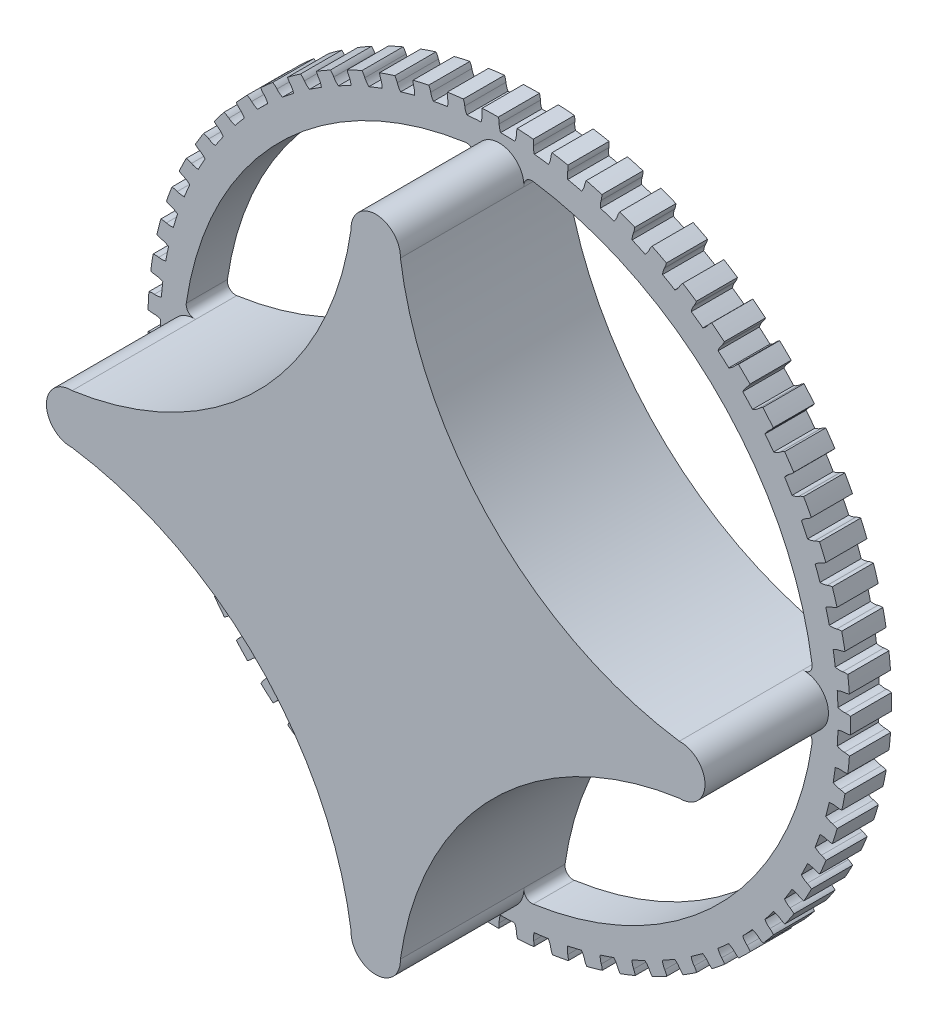
SolidWorks part; units mm, degrees
ref_plane "Alzado" through (0, 0, 0) normal (0, 0, 1) x (1, 0, 0)
ref_plane "Planta" through (0, 0, 0) normal (0, 1, 0) x (1, 0, 0)
ref_plane "Vista lateral" through (0, 0, 0) normal (1, 0, 0) x (0, 0, -1)
sketch "Croquis1" plane through (0, 0, 0) normal (0, 0, 1) x (1, 0, 0)
  circle A0 centre (0, 0) radius 40
  dimension "D1" = 80
extrude "Saliente-Extruir1" add sketch "Croquis1" along normal blind 5
sketch "Croquis2" plane through (0, 0, 5) normal (0, 0, 1) x (1, 0, 0)
  line L0 (0, 35.355) -> (35.355, -0.0007) construction
  line L1 (35.355, -0.0007) -> (0, -35.355) construction
  line L2 (0, -35.355) -> (-35.355, 0) construction
  line L3 (-35.355, 0) -> (0, 35.355) construction
  line L4 (0, 52.836) -> (0, -48.8534) construction
  line L5 (55.853, 0) -> (-59.1163, 0) construction
  arc A0 (36.8784, -2.9975) -> (36.8784, 2.9975) centre (37, 0) ccw
  circle A1 centre (0, 0) radius 35.355 construction
  arc A2 (-2.9975, 36.8784) -> (2.9975, 36.8784) centre (0, 37) cw
  circle A3 centre (0, 0) radius 40 construction
  arc A4 (36.8784, 2.9975) -> (2.9975, 36.8784) centre (42.5879, 42.5879) cw
  arc A5 (-36.8784, -2.9975) -> (-36.8784, 2.9975) centre (-37, 0) cw
  arc A6 (-36.8784, 2.9975) -> (-2.9975, 36.8784) centre (-42.5879, 42.5879) ccw
  arc A7 (36.8784, -2.9975) -> (2.9975, -36.8784) centre (42.5879, -42.5879) ccw
  arc A8 (-2.9975, -36.8784) -> (2.9975, -36.8784) centre (0, -37) ccw
  arc A9 (-36.8784, -2.9975) -> (-2.9975, -36.8784) centre (-42.5879, -42.5879) cw
  dimension "D2" = 70.71
  dimension "D3" = 3
  dimension "D5" = 3
  dimension "D7" = 40
  dimension "D1" = 50
  dimension "D4" = 37
  dimension "D6" = 37
extrude "Saliente-Extruir2" add sketch "Croquis2" along normal blind 15
sketch "Croquis3" plane through (0, 0, 5) normal (0, 0, 1) x (1, 0, 0)
  arc A0 (2.9975, -36.8784) -> (36.8784, -2.9975) centre (42.5879, -42.5879) cw
  arc A1 (2.9975, -36.8784) -> (4.13, -38.0109) centre (3.9873, -37.0211) ccw
  arc A2 (4.13, -38.0109) -> (38.0109, -4.13) centre (-1.5795, 1.5795) ccw
  arc A3 (36.8784, -2.9975) -> (38.0109, -4.13) centre (37.0211, -3.9873) cw
  arc A4 (36.8784, -2.9975) -> (2.9975, -36.8784) centre (42.5879, -42.5879) ccw construction
  arc A5 (-36.8784, -2.9975) -> (-2.9975, -36.8784) centre (-42.5879, -42.5879) cw
  arc A6 (-38.0109, -4.13) -> (-4.13, -38.0109) centre (1.5795, 1.5795) ccw
  arc A7 (-2.9975, -36.8784) -> (-4.13, -38.0109) centre (-3.9873, -37.0211) cw
  arc A8 (-36.8784, -2.9975) -> (-38.0109, -4.13) centre (-37.0211, -3.9873) ccw
  arc A9 (-2.9975, 36.8784) -> (-36.8784, 2.9975) centre (-42.5879, 42.5879) cw
  arc A10 (-4.13, 38.0109) -> (-38.0109, 4.13) centre (1.5795, -1.5795) ccw
  arc A11 (-36.8784, 2.9975) -> (-38.0109, 4.13) centre (-37.0211, 3.9873) cw
  arc A12 (-2.9975, 36.8784) -> (-4.13, 38.0109) centre (-3.9873, 37.0211) ccw
  arc A13 (36.8784, 2.9975) -> (2.9975, 36.8784) centre (42.5879, 42.5879) cw
  arc A14 (38.0109, 4.13) -> (4.13, 38.0109) centre (-1.5795, -1.5795) ccw
  arc A15 (2.9975, 36.8784) -> (4.13, 38.0109) centre (3.9873, 37.0211) cw
  arc A16 (36.8784, 2.9975) -> (38.0109, 4.13) centre (37.0211, 3.9873) ccw
  point P40 (0, 0)
  dimension "D1" = 40
  dimension "D2" = 1
  dimension "D3" = 4
extrude "Cortar-Extruir1" cut sketch "Croquis3" against normal blind 15
sketch "Croquis4" plane through (0, 0, 0) normal (0, 0, 1) x (1, 0, 0)
  circle A0 centre (0, 0) radius 40
  circle A1 centre (0, 0) radius 42.6665
  dimension "D1" = 85.333
  dimension "D2" = 80
extrude "Saliente-Extruir3" add sketch "Croquis4" along normal up to vertex
sketch "Croquis8" plane through (0, 0, 5) normal (0, 0, 1) x (1, 0, 0)
  arc A0 (2.1854, 42.6105) -> (-0.1088, 42.6664) centre (0, 0) ccw
  circle A3 centre (0, 0) radius 42.6665 construction
  arc A5 (0, 42) -> (-0.1088, 42.6664) centre (-2.0945, 42) ccw
  arc A6 (0, 42) -> (0.1731, 41.1661) centre (2.0945, 42) ccw
  arc A8 (6.4172, 42.1812) -> (4.1399, 42.4652) centre (0, 0) ccw
  arc A9 (1.9018, 41.1225) -> (2.0945, 42) centre (0, 42) ccw
  arc A10 (1.9018, 41.1225) -> (0.1731, 41.1661) centre (0, 0) ccw
  arc A11 (4.1818, 41.7913) -> (4.1399, 42.4652) centre (2.0978, 41.9998) ccw
  arc A12 (2.1854, 42.6105) -> (2.0945, 42) centre (4.189, 42) ccw
  arc A16 (6.4172, 42.1812) -> (6.2659, 41.5827) centre (8.35, 41.3742) ccw
  arc A17 (5.9869, 40.7288) -> (6.2659, 41.5827) centre (4.1818, 41.7913) ccw
  arc A18 (4.1818, 41.7913) -> (4.2711, 40.9443) centre (6.2659, 41.5827) ccw
  arc A19 (5.9869, 40.7288) -> (4.2711, 40.9443) centre (0, 0) ccw
  arc A20 (10.5852, 41.3326) -> (8.3475, 41.842) centre (0, 0) ccw
  arc A21 (8.3221, 41.1672) -> (8.3475, 41.842) centre (6.2692, 41.5823) ccw
  arc A22 (10.5852, 41.3326) -> (10.3751, 40.7522) centre (12.4281, 40.3372) ccw
  arc A23 (10.0124, 39.9303) -> (10.3751, 40.7522) centre (8.3221, 41.1672) ccw
  arc A24 (8.3221, 41.1672) -> (8.3266, 40.3156) centre (10.3751, 40.7522) ccw
  arc A25 (10.0124, 39.9303) -> (8.3266, 40.3156) centre (0, 0) ccw
  arc A26 (14.648, 40.0733) -> (12.4721, 40.8029) centre (0, 0) ccw
  arc A27 (12.3797, 40.1341) -> (12.4721, 40.8029) centre (10.3783, 40.7514) ccw
  arc A28 (14.648, 40.0733) -> (14.3812, 39.5167) centre (16.3826, 38.8993) ccw
  arc A29 (13.9384, 38.735) -> (14.3812, 39.5167) centre (12.3797, 40.1341) ccw
  arc A30 (12.3797, 40.1341) -> (12.2994, 39.2862) centre (14.3812, 39.5167) ccw
  arc A31 (13.9384, 38.735) -> (12.2994, 39.2862) centre (0, 0) ccw
  arc A32 (18.5652, 38.4157) -> (16.4728, 39.3583) centre (0, 0) ccw
  arc A33 (16.3143, 38.702) -> (16.4728, 39.3583) centre (14.3842, 39.5156) ccw
  arc A34 (18.5652, 38.4157) -> (18.2443, 37.8884) centre (20.1743, 37.0748) ccw
  arc A35 (17.7259, 37.1547) -> (18.2443, 37.8884) centre (16.3143, 38.702) ccw
  arc A36 (16.3143, 38.702) -> (16.1499, 37.8664) centre (18.2443, 37.8884) ccw
  arc A37 (17.7259, 37.1547) -> (16.1499, 37.8664) centre (0, 0) ccw
  arc A38 (22.2979, 36.3763) -> (20.3098, 37.5226) centre (0, 0) ccw
  arc A39 (20.0867, 36.8853) -> (20.3098, 37.5226) centre (18.2472, 37.887) ccw
  arc A40 (22.2979, 36.3763) -> (21.9261, 35.8836) centre (23.7655, 34.8819) ccw
  arc A41 (21.3373, 35.2051) -> (21.9261, 35.8836) centre (20.0867, 36.8853) ccw
  arc A42 (20.0867, 36.8853) -> (19.8399, 36.0702) centre (21.9261, 35.8836) ccw
  arc A43 (21.3373, 35.2051) -> (19.8399, 36.0702) centre (0, 0) ccw
  arc A44 (25.809, 33.9753) -> (23.9449, 35.3139) centre (0, 0) ccw
  arc A45 (23.6594, 34.702) -> (23.9449, 35.3139) centre (21.9289, 35.8819) ccw
  arc A46 (25.809, 33.9753) -> (25.39, 33.5222) centre (27.1206, 32.3423) ccw
  arc A47 (24.7365, 32.9057) -> (25.39, 33.5222) centre (23.6594, 34.702) ccw
  arc A48 (23.6594, 34.702) -> (23.3328, 33.9155) centre (25.39, 33.5222) ccw
  arc A49 (24.7365, 32.9057) -> (23.3328, 33.9155) centre (0, 0) ccw
  arc A50 (29.0636, 31.2368) -> (27.342, 32.7543) centre (0, 0) ccw
  arc A51 (26.9971, 32.1739) -> (27.342, 32.7543) centre (25.3926, 33.5202) ccw
  arc A52 (29.0636, 31.2368) -> (28.6016, 30.8275) centre (30.206, 29.4812) ccw
  arc A53 (27.89, 30.2792) -> (28.6016, 30.8275) centre (26.9971, 32.1739) ccw
  arc A54 (26.9971, 32.1739) -> (26.5937, 31.4238) centre (28.6016, 30.8275) ccw
  arc A55 (27.89, 30.2792) -> (26.5937, 31.4238) centre (0, 0) ccw
  arc A56 (32.0294, 28.1877) -> (30.4674, 29.8691) centre (0, 0) ccw
  arc A57 (30.0664, 29.3259) -> (30.4674, 29.8691) centre (28.604, 30.8253) ccw
  arc A58 (32.0294, 28.1877) -> (31.5289, 27.8266) centre (32.9913, 26.3272) ccw
  arc A59 (30.7662, 27.3518) -> (31.5289, 27.8266) centre (30.0664, 29.3259) ccw
  arc A60 (30.0664, 29.3259) -> (29.5904, 28.6198) centre (31.5289, 27.8266) ccw
  arc A61 (30.7662, 27.3518) -> (29.5904, 28.6198) centre (0, 0) ccw
  arc A62 (34.6768, 24.8586) -> (33.2901, 26.6871) centre (0, 0) ccw
  arc A63 (32.8369, 26.1866) -> (33.2901, 26.6871) centre (31.531, 27.8241) ccw
  arc A64 (34.6768, 24.8586) -> (34.1428, 24.549) centre (35.4487, 22.9115) ccw
  arc A65 (33.3367, 24.1526) -> (34.1428, 24.549) centre (32.8369, 26.1866) ccw
  arc A66 (32.8369, 26.1866) -> (32.2929, 25.5313) centre (34.1428, 24.549) ccw
  arc A67 (33.3367, 24.1526) -> (32.2929, 25.5313) centre (0, 0) ccw
  arc A68 (36.9796, 21.2823) -> (35.7818, 23.2399) centre (0, 0) ccw
  arc A69 (35.2811, 22.7869) -> (35.7818, 23.2399) centre (34.1447, 24.5464) ccw
  arc A70 (36.9796, 21.2823) -> (36.4175, 21.0275) centre (37.5538, 19.2681) ccw
  arc A71 (35.5758, 20.7133) -> (36.4175, 21.0275) centre (35.2811, 22.7869) ccw
  arc A72 (35.2811, 22.7869) -> (34.6746, 22.1891) centre (36.4175, 21.0275) ccw
  arc A73 (35.5758, 20.7133) -> (34.6746, 22.1891) centre (0, 0) ccw
  arc A74 (38.9149, 17.4946) -> (37.9179, 19.5617) centre (0, 0) ccw
  arc A75 (37.3746, 19.1608) -> (37.9179, 19.5617) centre (36.4191, 21.0247) ccw
  arc A76 (38.9149, 17.4946) -> (38.3301, 17.297) centre (39.2857, 15.4332) ccw
  arc A77 (37.4614, 17.0681) -> (38.3301, 17.297) centre (37.3746, 19.1608) ccw
  arc A78 (37.3746, 19.1608) -> (36.7116, 18.6264) centre (38.3301, 17.297) ccw
  arc A79 (37.4614, 17.0681) -> (36.7116, 18.6264) centre (0, 0) ccw
  arc A80 (40.4634, 13.533) -> (39.6772, 15.6891) centre (0, 0) ccw
  arc A81 (39.0967, 15.3443) -> (39.6772, 15.6891) centre (38.3315, 17.294) ccw
  arc A82 (40.4634, 13.533) -> (39.8619, 13.3946) centre (40.6271, 11.4449) ccw
  arc A83 (38.9747, 13.2534) -> (39.8619, 13.3946) centre (39.0967, 15.3443) ccw
  arc A84 (39.0967, 15.3443) -> (38.3837, 14.8785) centre (39.8619, 13.3946) ccw
  arc A85 (38.9747, 13.2534) -> (38.3837, 14.8785) centre (0, 0) ccw
  arc A86 (41.6098, 9.4369) -> (41.0422, 11.6605) centre (0, 0) ccw
  arc A87 (40.4302, 11.3753) -> (41.0422, 11.6605) centre (39.8629, 13.3915) ccw
  arc A88 (41.6098, 9.4369) -> (40.9975, 9.3591) centre (41.5648, 7.3429) ccw
  arc A89 (40.1007, 9.3069) -> (40.9975, 9.3591) centre (40.4302, 11.3753) ccw
  arc A90 (40.4302, 11.3753) -> (39.6744, 10.9828) centre (40.9975, 9.3591) ccw
  arc A91 (40.1007, 9.3069) -> (39.6744, 10.9828) centre (0, 0) ccw
  arc A92 (42.3426, 5.247) -> (41.9993, 7.5161) centre (0, 0) ccw
  arc A93 (41.3619, 7.2932) -> (41.9993, 7.5161) centre (40.9982, 9.3559) ccw
  arc A94 (42.3426, 5.247) -> (41.7256, 5.2305) centre (42.0893, 3.1679) ccw
  arc A95 (40.8281, 5.2679) -> (41.7256, 5.2305) centre (41.3619, 7.2932) ccw
  arc A96 (41.3619, 7.2932) -> (40.5708, 6.9779) centre (41.7256, 5.2305) ccw
  arc A97 (40.8281, 5.2679) -> (40.5708, 6.9779) centre (0, 0) ccw
  arc A98 (42.6547, 1.005) -> (42.5389, 3.297) centre (0, 0) ccw
  arc A99 (41.8826, 3.1387) -> (42.5389, 3.297) centre (41.726, 5.2273) ccw
  arc A100 (42.6547, 1.005) -> (42.0391, 1.05) centre (42.1956, -1.0386) ccw
  arc A101 (41.1497, 1.1766) -> (42.0391, 1.05) centre (41.8826, 3.1387) ccw
  arc A102 (41.8826, 3.1387) -> (41.064, 2.9037) centre (42.0391, 1.05) ccw
  arc A103 (41.1497, 1.1766) -> (41.064, 2.9037) centre (0, 0) ccw
  arc A104 (42.5428, -3.2471) -> (42.6558, -0.9549) centre (0, 0) ccw
  arc A105 (41.9869, -1.0471) -> (42.6558, -0.9549) centre (42.0392, 1.0468) ccw
  arc A106 (42.5428, -3.2471) -> (41.9347, -3.1409) centre (41.8825, -5.2348) ccw
  arc A107 (41.0623, -2.9265) -> (41.9347, -3.1409) centre (41.9869, -1.0471) ccw
  arc A108 (41.9869, -1.0471) -> (41.149, -1.1994) centre (41.9347, -3.1409) ccw
  arc A109 (41.0623, -2.9265) -> (41.149, -1.1994) centre (0, 0) ccw
  arc A110 (42.0081, -7.4668) -> (42.3488, -5.1973) centre (0, 0) ccw
  arc A111 (41.674, -5.2224) -> (42.3488, -5.1973) centre (41.9345, -3.1442) ccw
  arc A112 (42.0081, -7.4668) -> (41.4136, -7.3007) centre (41.1532, -9.3789) ccw
  arc A113 (40.5669, -7.0004) -> (41.4136, -7.3007) centre (41.674, -5.2224) ccw
  arc A114 (41.674, -5.2224) -> (40.8251, -5.2906) centre (41.4136, -7.3007) ccw
  arc A115 (40.5669, -7.0004) -> (40.8251, -5.2906) centre (0, 0) ccw
  arc A116 (41.0559, -11.6124) -> (41.6208, -9.3881) centre (0, 0) ccw
  arc A117 (40.947, -9.3459) -> (41.6208, -9.3881) centre (41.413, -7.3039) ccw
  arc A118 (41.0559, -11.6124) -> (40.4809, -11.3879) centre (40.0148, -13.4299) ccw
  arc A119 (39.6683, -11.0048) -> (40.4809, -11.3879) centre (40.947, -9.3459) ccw
  arc A120 (40.947, -9.3459) -> (40.0955, -9.3291) centre (40.4809, -11.3879) ccw
  arc A121 (39.6683, -11.0048) -> (40.0955, -9.3291) centre (0, 0) ccw
  arc A122 (39.6956, -15.6425) -> (40.4793, -13.4855) centre (0, 0) ccw
  arc A123 (39.8129, -13.3764) -> (40.4793, -13.4855) centre (40.48, -11.391) ccw
  arc A124 (39.6956, -15.6425) -> (39.1459, -15.3619) centre (38.4788, -17.3473) ccw
  arc A125 (38.3755, -14.8998) -> (39.1459, -15.3619) centre (39.8129, -13.3764) ccw
  arc A126 (39.8129, -13.3764) -> (38.9674, -13.275) centre (39.1459, -15.3619) ccw
  arc A127 (38.3755, -14.8998) -> (38.9674, -13.275) centre (0, 0) ccw
  arc A128 (37.9409, -19.5172) -> (38.9354, -17.4489) centre (0, 0) ccw
  arc A129 (38.2832, -17.2741) -> (38.9354, -17.4489) centre (39.1447, -15.3649) ccw
  arc A130 (37.9409, -19.5172) -> (37.4218, -19.1832) centre (36.5604, -21.0924) ccw
  arc A131 (36.7012, -18.6467) -> (37.4218, -19.1832) centre (38.2832, -17.2741) ccw
  arc A132 (38.2832, -17.2741) -> (37.452, -17.0889) centre (37.4218, -19.1832) ccw
  arc A133 (36.7012, -18.6467) -> (37.452, -17.0889) centre (0, 0) ccw
  arc A134 (35.809, -23.1979) -> (37.0046, -21.2389) centre (0, 0) ccw
  arc A135 (36.3731, -21) -> (37.0046, -21.2389) centre (37.4203, -19.1861) ccw
  arc A136 (35.809, -23.1979) -> (35.3258, -22.8139) centre (34.2786, -24.6278) ccw
  arc A137 (34.6622, -22.2083) -> (35.3258, -22.8139) centre (36.3731, -21) ccw
  arc A138 (36.3731, -21) -> (35.5643, -20.733) centre (35.3258, -22.8139) ccw
  arc A139 (34.6622, -22.2083) -> (35.5643, -20.733) centre (0, 0) ccw
  arc A140 (33.3213, -26.6481) -> (34.706, -24.8179) centre (0, 0) ccw
  arc A141 (34.1014, -24.5172) -> (34.706, -24.8179) centre (35.324, -22.8166) ccw
  arc A142 (33.3213, -26.6481) -> (32.8787, -26.2178) centre (31.6561, -27.9184) ccw
  arc A143 (32.2788, -25.5492) -> (32.8787, -26.2178) centre (34.1014, -24.5172) ccw
  arc A144 (34.1014, -24.5172) -> (33.3233, -24.1711) centre (32.8787, -26.2178) ccw
  arc A145 (32.2788, -25.5492) -> (33.3233, -24.1711) centre (0, 0) ccw
  arc A146 (30.5025, -29.8334) -> (32.0624, -28.1501) centre (0, 0) ccw
  arc A147 (31.4908, -27.7908) -> (32.0624, -28.1501) centre (32.8767, -26.2204) ccw
  arc A148 (30.5025, -29.8334) -> (30.1049, -29.3612) centre (28.719, -30.9316) ccw
  arc A149 (29.5745, -28.6362) -> (30.1049, -29.3612) centre (31.4908, -27.7908) ccw
  arc A150 (31.4908, -27.7908) -> (30.751, -27.3689) centre (30.1049, -29.3612) ccw
  arc A151 (29.5745, -28.6362) -> (30.751, -27.3689) centre (0, 0) ccw
  arc A152 (27.3805, -32.7222) -> (29.1003, -31.2026) centre (0, 0) ccw
  arc A153 (28.5673, -30.7882) -> (29.1003, -31.2026) centre (30.1026, -29.3636) ccw
  arc A154 (27.3805, -32.7222) -> (27.0319, -32.2128) centre (25.4965, -33.6374) ccw
  arc A155 (26.5763, -31.4385) -> (27.0319, -32.2128) centre (28.5673, -30.7882) ccw
  arc A156 (28.5673, -30.7882) -> (27.8732, -30.2947) centre (27.0319, -32.2128) ccw
  arc A157 (26.5763, -31.4385) -> (27.8732, -30.2947) centre (0, 0) ccw
  arc A158 (23.9863, -35.2858) -> (25.8489, -33.945) centre (0, 0) ccw
  arc A159 (25.3598, -33.4796) -> (25.8489, -33.945) centre (27.0294, -32.2149) ccw
  arc A160 (23.9863, -35.2858) -> (23.6902, -34.7442) centre (22.0206, -36.0089) ccw
  arc A161 (23.314, -33.9285) -> (23.6902, -34.7442) centre (25.3598, -33.4796) ccw
  arc A162 (25.3598, -33.4796) -> (24.7183, -32.9194) centre (23.6902, -34.7442) ccw
  arc A163 (23.314, -33.9285) -> (24.7183, -32.9194) centre (0, 0) ccw
  arc A164 (20.3538, -37.4987) -> (22.3406, -36.3501) centre (0, 0) ccw
  arc A165 (21.9003, -35.8382) -> (22.3406, -36.3501) centre (23.6875, -34.7461) ccw
  arc A166 (20.3538, -37.4987) -> (20.1131, -36.9304) centre (18.3258, -38.0225) ccw
  arc A167 (19.8199, -36.0812) -> (20.1131, -36.9304) centre (21.9003, -35.8382) ccw
  arc A168 (21.9003, -35.8382) -> (21.3177, -35.217) centre (20.1131, -36.9304) ccw
  arc A169 (19.8199, -36.0812) -> (21.3177, -35.217) centre (0, 0) ccw
  arc A170 (16.519, -39.339) -> (18.6103, -38.3938) centre (0, 0) ccw
  arc A171 (18.2231, -37.8407) -> (18.6103, -38.3938) centre (20.1102, -36.9319) ccw
  arc A172 (16.519, -39.339) -> (16.336, -38.7495) centre (14.449, -39.6582) ccw
  arc A173 (16.1289, -37.8753) -> (16.336, -38.7495) centre (18.2231, -37.8407) ccw
  arc A174 (18.2231, -37.8407) -> (17.7053, -37.1645) centre (16.336, -38.7495) ccw
  arc A175 (16.1289, -37.8753) -> (17.7053, -37.1645) centre (0, 0) ccw
  arc A176 (12.52, -40.7882) -> (14.695, -40.056) centre (0, 0) ccw
  arc A177 (14.3648, -39.4671) -> (14.695, -40.056) centre (16.333, -38.7507) ccw
  arc A178 (12.52, -40.7882) -> (12.3967, -40.1835) centre (10.4285, -40.8998) ccw
  arc A179 (12.2776, -39.293) -> (12.3967, -40.1835) centre (14.3648, -39.4671) ccw
  arc A180 (14.3648, -39.4671) -> (13.9169, -38.7427) centre (12.3967, -40.1835) ccw
  arc A181 (12.2776, -39.293) -> (13.9169, -38.7427) centre (0, 0) ccw
  arc A182 (8.3966, -41.8321) -> (10.6337, -41.3201) centre (0, 0) ccw
  arc A183 (10.3638, -40.7012) -> (10.6337, -41.3201) centre (12.3935, -40.1844) ccw
  arc A184 (8.3966, -41.8321) -> (8.3341, -41.2181) centre (6.3043, -41.7349) ccw
  arc A185 (8.3043, -40.3202) -> (8.3341, -41.2181) centre (10.3638, -40.7012) ccw
  arc A186 (10.3638, -40.7012) -> (9.9903, -39.9359) centre (8.3341, -41.2181) ccw
  arc A187 (8.3043, -40.3202) -> (9.9903, -39.9359) centre (0, 0) ccw
  arc A188 (4.1897, -42.4603) -> (6.4667, -42.1736) centre (0, 0) ccw
  arc A189 (6.2598, -41.5309) -> (6.4667, -42.1736) centre (8.3309, -41.2187) ccw
  arc A190 (4.1897, -42.4603) -> (4.1887, -41.8431) centre (2.1176, -42.1552) ccw
  arc A191 (4.2484, -40.9467) -> (4.1887, -41.8431) centre (6.2598, -41.5309) ccw
  arc A192 (6.2598, -41.5309) -> (5.9643, -40.7322) centre (4.1887, -41.8431) ccw
  arc A193 (4.2484, -40.9467) -> (5.9643, -40.7322) centre (0, 0) ccw
  arc A194 (-0.0588, -42.6665) -> (2.2354, -42.6079) centre (0, 0) ccw
  arc A195 (2.0935, -41.9478) -> (2.2354, -42.6079) centre (4.1854, -41.8434) ccw
  arc A196 (-0.0588, -42.6665) -> (0.0016, -42.0522) centre (-2.0903, -42.1566) ccw
  arc A197 (0.1503, -41.1662) -> (0.0016, -42.0522) centre (2.0935, -41.9478) ccw
  arc A198 (2.0935, -41.9478) -> (1.879, -41.1236) centre (0.0016, -42.0522) ccw
  arc A199 (0.1503, -41.1662) -> (1.879, -41.1236) centre (0, 0) ccw
  arc A200 (-4.3067, -42.4486) -> (-2.018, -42.6187) centre (0, 0) ccw
  arc A201 (-2.0935, -41.9478) -> (-2.018, -42.6187) centre (-0.0016, -42.0522) ccw
  arc A202 (-4.3067, -42.4486) -> (-4.1854, -41.8434) centre (-6.2773, -41.739) ccw
  arc A203 (-3.9493, -40.9766) -> (-4.1854, -41.8434) centre (-2.0935, -41.9478) ccw
  arc A204 (-2.0935, -41.9478) -> (-2.2249, -41.1063) centre (-4.1854, -41.8434) ccw
  arc A205 (-3.9493, -40.9766) -> (-2.2249, -41.1063) centre (0, 0) ccw
  arc A206 (-8.5118, -41.8088) -> (-6.2515, -42.206) centre (0, 0) ccw
  arc A207 (-6.2598, -41.5309) -> (-6.2515, -42.206) centre (-4.1887, -41.8431) ccw
  arc A208 (-8.5118, -41.8088) -> (-8.3309, -41.2187) centre (-10.402, -40.9066) ccw
  arc A209 (-8.0096, -40.3798) -> (-8.3309, -41.2187) centre (-6.2598, -41.5309) ccw
  arc A210 (-6.2598, -41.5309) -> (-6.3067, -40.6805) centre (-8.3309, -41.2187) ccw
  arc A211 (-8.0096, -40.3798) -> (-6.3067, -40.6805) centre (0, 0) ccw
  arc A212 (-12.6323, -40.7536) -> (-10.4228, -41.3739) centre (0, 0) ccw
  arc A213 (-10.3638, -40.7012) -> (-10.4228, -41.3739) centre (-8.3341, -41.2181) ccw
  arc A214 (-12.6323, -40.7536) -> (-12.3935, -40.1844) centre (-14.4233, -39.6676) ccw
  arc A215 (-11.9903, -39.3816) -> (-12.3935, -40.1844) centre (-10.3638, -40.7012) ccw
  arc A216 (-10.3638, -40.7012) -> (-10.3258, -39.8504) centre (-12.3935, -40.1844) ccw
  arc A217 (-11.9903, -39.3816) -> (-10.3258, -39.8504) centre (0, 0) ccw
  arc A218 (-16.6273, -39.2933) -> (-14.4905, -40.1305) centre (0, 0) ccw
  arc A219 (-14.3648, -39.4671) -> (-14.4905, -40.1305) centre (-12.3967, -40.1835) ccw
  arc A220 (-16.6273, -39.2933) -> (-16.333, -38.7507) centre (-18.3012, -38.0344) ccw
  arc A221 (-15.8519, -37.9921) -> (-16.333, -38.7507) centre (-14.3648, -39.4671) ccw
  arc A222 (-14.3648, -39.4671) -> (-14.2424, -38.6243) centre (-16.333, -38.7507) ccw
  arc A223 (-15.8519, -37.9921) -> (-14.2424, -38.6243) centre (0, 0) ccw
  arc A224 (-20.457, -37.4425) -> (-18.4142, -38.4883) centre (0, 0) ccw
  arc A225 (-18.2231, -37.8407) -> (-18.4142, -38.4883) centre (-16.336, -38.7495) ccw
  arc A226 (-20.457, -37.4425) -> (-20.1102, -36.9319) centre (-21.9973, -36.0232) ccw
  arc A227 (-19.5559, -36.225) -> (-20.1102, -36.9319) centre (-18.2231, -37.8407) ccw
  arc A228 (-18.2231, -37.8407) -> (-18.0173, -37.0143) centre (-20.1102, -36.9319) ccw
  arc A229 (-19.5559, -36.225) -> (-18.0173, -37.0143) centre (0, 0) ccw
  arc A230 (-24.0834, -35.2196) -> (-22.1549, -36.4636) centre (0, 0) ccw
  arc A231 (-21.9003, -35.8382) -> (-22.1549, -36.4636) centre (-20.1131, -36.9304) ccw
  arc A232 (-24.0834, -35.2196) -> (-23.6875, -34.7461) centre (-25.4747, -33.6539) ccw
  arc A233 (-23.0656, -34.0978) -> (-23.6875, -34.7461) centre (-21.9003, -35.8382) ccw
  arc A234 (-21.9003, -35.8382) -> (-21.6132, -35.0364) centre (-23.6875, -34.7461) ccw
  arc A235 (-23.0656, -34.0978) -> (-21.6132, -35.0364) centre (0, 0) ccw
  arc A236 (-27.4705, -32.6466) -> (-25.6754, -34.0765) centre (0, 0) ccw
  arc A237 (-25.3598, -33.4796) -> (-25.6754, -34.0765) centre (-23.6902, -34.7442) ccw
  arc A238 (-27.4705, -32.6466) -> (-27.0294, -32.2149) centre (-28.699, -30.9502) ccw
  arc A239 (-26.346, -31.6318) -> (-27.0294, -32.2149) centre (-25.3598, -33.4796) ccw
  arc A240 (-25.3598, -33.4796) -> (-24.9943, -32.7103) centre (-27.0294, -32.2149) ccw
  arc A241 (-26.346, -31.6318) -> (-24.9943, -32.7103) centre (0, 0) ccw
  arc A242 (-30.5845, -29.7492) -> (-28.9407, -31.3507) centre (0, 0) ccw
  arc A243 (-28.5673, -30.7882) -> (-28.9407, -31.3507) centre (-27.0319, -32.2128) ccw
  arc A244 (-30.5845, -29.7492) -> (-30.1026, -29.3636) centre (-31.638, -27.9389) ccw
  arc A245 (-29.3646, -28.8514) -> (-30.1026, -29.3636) centre (-28.5673, -30.7882) ccw
  arc A246 (-28.5673, -30.7882) -> (-28.127, -30.0591) centre (-30.1026, -29.3636) ccw
  arc A247 (-29.3646, -28.8514) -> (-28.127, -30.0591) centre (0, 0) ccw
  arc A248 (-33.3946, -26.5562) -> (-31.9184, -28.3133) centre (0, 0) ccw
  arc A249 (-31.4908, -27.7908) -> (-31.9184, -28.3133) centre (-30.1049, -29.3612) ccw
  arc A250 (-33.3946, -26.5562) -> (-32.8767, -26.2204) centre (-34.2626, -24.65) ccw
  arc A251 (-32.0913, -25.7842) -> (-32.8767, -26.2204) centre (-31.4908, -27.7908) ccw
  arc A252 (-31.4908, -27.7908) -> (-30.9802, -27.1092) centre (-32.8767, -26.2204) ccw
  arc A253 (-32.0913, -25.7842) -> (-30.9802, -27.1092) centre (0, 0) ccw
  arc A254 (-35.8728, -23.0992) -> (-34.5789, -24.9946) centre (0, 0) ccw
  arc A255 (-34.1014, -24.5172) -> (-34.5789, -24.9946) centre (-32.8787, -26.2178) ccw
  arc A256 (-35.8728, -23.0992) -> (-35.324, -22.8166) centre (-36.5467, -21.116) ccw
  arc A257 (-34.4991, -22.4608) -> (-35.324, -22.8166) centre (-34.1014, -24.5172) ccw
  arc A258 (-34.1014, -24.5172) -> (-33.5254, -23.8899) centre (-35.324, -22.8166) ccw
  arc A259 (-34.4991, -22.4608) -> (-33.5254, -23.8899) centre (0, 0) ccw
  arc A260 (-37.9945, -19.4126) -> (-36.8957, -21.4274) centre (0, 0) ccw
  arc A261 (-36.3731, -21) -> (-36.8957, -21.4274) centre (-35.3258, -22.8139) ccw
  arc A262 (-37.9945, -19.4126) -> (-37.4203, -19.1861) centre (-38.4676, -17.3722) ccw
  arc A263 (-36.5641, -18.9142) -> (-37.4203, -19.1861) centre (-36.3731, -21) ccw
  arc A264 (-36.3731, -21) -> (-35.7375, -20.4331) centre (-37.4203, -19.1861) ccw
  arc A265 (-36.5641, -18.9142) -> (-35.7375, -20.4331) centre (0, 0) ccw
  arc A266 (-39.7386, -15.5331) -> (-38.8459, -17.6473) centre (0, 0) ccw
  arc A267 (-38.2832, -17.2741) -> (-38.8459, -17.6473) centre (-37.4218, -19.1832) ccw
  arc A268 (-39.7386, -15.5331) -> (-39.1447, -15.3649) centre (-40.0061, -13.4558) ccw
  arc A269 (-38.2656, -15.1796) -> (-39.1447, -15.3649) centre (-38.2832, -17.2741) ccw
  arc A270 (-38.2832, -17.2741) -> (-37.5944, -16.7733) centre (-39.1447, -15.3649) ccw
  arc A271 (-38.2656, -15.1796) -> (-37.5944, -16.7733) centre (0, 0) ccw
  arc A272 (-41.0877, -11.4992) -> (-40.41, -13.6918) centre (0, 0) ccw
  arc A273 (-39.8129, -13.3764) -> (-40.41, -13.6918) centre (-39.1459, -15.3619) ccw
  arc A274 (-41.0877, -11.4992) -> (-40.48, -11.391) centre (-41.1471, -9.4056) ccw
  arc A275 (-39.5869, -11.2942) -> (-40.48, -11.391) centre (-39.8129, -13.3764) ccw
  arc A276 (-39.8129, -13.3764) -> (-39.0777, -12.9467) centre (-40.48, -11.391) ccw
  arc A277 (-39.5869, -11.2942) -> (-39.0777, -12.9467) centre (0, 0) ccw
  arc A278 (-42.0285, -7.3511) -> (-41.5724, -9.6003) centre (0, 0) ccw
  arc A279 (-40.947, -9.3459) -> (-41.5724, -9.6003) centre (-40.4809, -11.3879) ccw
  arc A280 (-42.0285, -7.3511) -> (-41.413, -7.3039) centre (-41.8791, -5.2619) ccw
  arc A281 (-40.5147, -7.2965) -> (-41.413, -7.3039) centre (-40.947, -9.3459) ccw
  arc A282 (-40.947, -9.3459) -> (-40.1725, -8.9915) centre (-41.413, -7.3039) ccw
  arc A283 (-40.5147, -7.2965) -> (-40.1725, -8.9915) centre (0, 0) ccw
  arc A284 (-42.5515, -3.1299) -> (-42.3217, -5.4133) centre (0, 0) ccw
  arc A285 (-41.674, -5.2224) -> (-42.3217, -5.4133) centre (-41.4136, -7.3007) ccw
  arc A286 (-42.5515, -3.1299) -> (-41.9345, -3.1442) centre (-42.1949, -1.0659) ccw
  arc A287 (-41.0399, -3.2262) -> (-41.9345, -3.1442) centre (-41.674, -5.2224) ccw
  arc A288 (-41.674, -5.2224) -> (-40.8682, -4.9469) centre (-41.9345, -3.1442) ccw
  arc A289 (-41.0399, -3.2262) -> (-40.8682, -4.9469) centre (0, 0) ccw
  arc A290 (-42.6517, 1.1225) -> (-42.6504, -1.1725) centre (0, 0) ccw
  arc A291 (-41.9869, -1.0471) -> (-42.6504, -1.1725) centre (-41.9347, -3.1409) ccw
  arc A292 (-42.6517, 1.1225) -> (-42.0392, 1.0468) centre (-42.0914, 3.1406) ccw
  arc A293 (-41.1572, 0.876) -> (-42.0392, 1.0468) centre (-41.9869, -1.0471) ccw
  arc A294 (-41.9869, -1.0471) -> (-41.1577, -0.8532) centre (-42.0392, 1.0468) ccw
  arc A295 (-41.1572, 0.876) -> (-41.1577, -0.8532) centre (0, 0) ccw
  arc A296 (-42.328, 5.3636) -> (-42.5552, 3.0799) centre (0, 0) ccw
  arc A297 (-41.8826, 3.1387) -> (-42.5552, 3.0799) centre (-42.0391, 1.05) ccw
  arc A298 (-42.328, 5.3636) -> (-41.726, 5.2273) centre (-41.5695, 7.316) ccw
  arc A299 (-40.8654, 4.9696) -> (-41.726, 5.2273) centre (-41.8826, 3.1387) ccw
  arc A300 (-41.8826, 3.1387) -> (-41.0381, 3.249) centre (-41.726, 5.2273) ccw
  arc A301 (-40.8654, 4.9696) -> (-41.0381, 3.249) centre (0, 0) ccw
  arc A302 (-41.5836, 9.5515) -> (-42.0371, 7.3018) centre (0, 0) ccw
  arc A303 (-41.3619, 7.2932) -> (-42.0371, 7.3018) centre (-41.7256, 5.2305) ccw
  arc A304 (-41.5836, 9.5515) -> (-40.9982, 9.3559) centre (-40.6345, 11.4186) ccw
  arc A305 (-40.1675, 9.0138) -> (-40.9982, 9.3559) centre (-41.3619, 7.2932) ccw
  arc A306 (-41.3619, 7.2932) -> (-40.5107, 7.3189) centre (-40.9982, 9.3559) ccw
  arc A307 (-40.1675, 9.0138) -> (-40.5107, 7.3189) centre (0, 0) ccw
  arc A308 (-40.426, 13.6444) -> (-41.1011, 11.451) centre (0, 0) ccw
  arc A309 (-40.4302, 11.3753) -> (-41.1011, 11.451) centre (-40.9975, 9.3591) ccw
  arc A310 (-40.426, 13.6444) -> (-39.8629, 13.3915) centre (-39.2957, 15.4077) ccw
  arc A311 (-39.0705, 12.9684) -> (-39.8629, 13.3915) centre (-40.4302, 11.3753) ccw
  arc A312 (-40.4302, 11.3753) -> (-39.5806, 11.3161) centre (-39.8629, 13.3915) ccw
  arc A313 (-39.0705, 12.9684) -> (-39.5806, 11.3161) centre (0, 0) ccw
  arc A314 (-38.8666, 17.6017) -> (-39.7568, 15.4865) centre (0, 0) ccw
  arc A315 (-39.0967, 15.3443) -> (-39.7568, 15.4865) centre (-39.8619, 13.3946) ccw
  arc A316 (-38.8666, 17.6017) -> (-38.3315, 17.294) centre (-37.5663, 19.2438) ccw
  arc A317 (-37.5851, 16.7941) -> (-38.3315, 17.294) centre (-39.0967, 15.3443) ccw
  arc A318 (-39.0967, 15.3443) -> (-38.2572, 15.2009) centre (-38.3315, 17.294) ccw
  arc A319 (-37.5851, 16.7941) -> (-38.2572, 15.2009) centre (0, 0) ccw
  arc A320 (-36.9209, 21.3841) -> (-38.0172, 19.368) centre (0, 0) ccw
  arc A321 (-37.3746, 19.1608) -> (-38.0172, 19.368) centre (-38.3301, 17.297) ccw
  arc A322 (-36.9209, 21.3841) -> (-36.4191, 21.0247) centre (-35.4635, 22.8885) ccw
  arc A323 (-35.7262, 20.4529) -> (-36.4191, 21.0247) centre (-37.3746, 19.1608) ccw
  arc A324 (-37.3746, 19.1608) -> (-36.5536, 18.9345) centre (-36.4191, 21.0247) ccw
  arc A325 (-35.7262, 20.4529) -> (-36.5536, 18.9345) centre (0, 0) ccw
  arc A326 (-34.6082, 24.954) -> (-35.8999, 23.0571) centre (0, 0) ccw
  arc A327 (-35.2811, 22.7869) -> (-35.8999, 23.0571) centre (-36.4175, 21.0275) ccw
  arc A328 (-34.6082, 24.954) -> (-34.1447, 24.5464) centre (-33.0084, 26.3058) ccw
  arc A329 (-33.5122, 23.9085) -> (-34.1447, 24.5464) centre (-35.2811, 22.7869) ccw
  arc A330 (-35.2811, 22.7869) -> (-34.4867, 22.48) centre (-34.1447, 24.5464) ccw
  arc A331 (-33.5122, 23.9085) -> (-34.4867, 22.48) centre (0, 0) ccw
  arc A332 (-31.9516, 28.2759) -> (-33.4258, 26.517) centre (0, 0) ccw
  arc A333 (-32.8369, 26.1866) -> (-33.4258, 26.517) centre (-34.1428, 24.549) ccw
  arc A334 (-31.9516, 28.2759) -> (-31.531, 27.8241) centre (-30.2251, 29.4617) ccw
  arc A335 (-30.9651, 27.1264) -> (-31.531, 27.8241) centre (-32.8369, 26.1866) ccw
  arc A336 (-32.8369, 26.1866) -> (-32.077, 25.802) centre (-31.531, 27.8241) ccw
  arc A337 (-30.9651, 27.1264) -> (-32.077, 25.802) centre (0, 0) ccw
  arc A338 (-28.9775, 31.3167) -> (-30.6194, 29.7133) centre (0, 0) ccw
  arc A339 (-30.0664, 29.3259) -> (-30.6194, 29.7133) centre (-31.5289, 27.8266) ccw
  arc A340 (-28.9775, 31.3167) -> (-28.604, 30.8253) centre (-27.1415, 32.3247) ccw
  arc A341 (-28.1103, 30.0747) -> (-28.604, 30.8253) centre (-30.0664, 29.3259) ccw
  arc A342 (-30.0664, 29.3259) -> (-29.3486, 28.8677) centre (-28.604, 30.8253) ccw
  arc A343 (-28.1103, 30.0747) -> (-29.3486, 28.8677) centre (0, 0) ccw
  arc A344 (-25.7153, 34.0463) -> (-27.5088, 32.6144) centre (0, 0) ccw
  arc A345 (-26.9971, 32.1739) -> (-27.5088, 32.6144) centre (-28.6016, 30.8275) ccw
  arc A346 (-25.7153, 34.0463) -> (-25.3926, 33.5202) centre (-23.7881, 34.8665) ccw
  arc A347 (-24.9762, 32.7242) -> (-25.3926, 33.5202) centre (-26.9971, 32.1739) ccw
  arc A348 (-26.9971, 32.1739) -> (-26.3284, 31.6464) centre (-25.3926, 33.5202) ccw
  arc A349 (-24.9762, 32.7242) -> (-26.3284, 31.6464) centre (0, 0) ccw
  arc A350 (-22.1976, 36.4375) -> (-24.1247, 35.1913) centre (0, 0) ccw
  arc A351 (-23.6594, 34.702) -> (-24.1247, 35.1913) centre (-25.39, 33.5222) ccw
  arc A352 (-22.1976, 36.4375) -> (-21.9289, 35.8819) centre (-20.1983, 37.0618) ccw
  arc A353 (-21.5938, 35.0484) -> (-21.9289, 35.8819) centre (-23.6594, 34.702) ccw
  arc A354 (-23.6594, 34.702) -> (-23.0467, 34.1106) centre (-21.9289, 35.8819) ccw
  arc A355 (-21.5938, 35.0484) -> (-23.0467, 34.1106) centre (0, 0) ccw
  arc A356 (-18.4593, 38.4667) -> (-20.5009, 37.4185) centre (0, 0) ccw
  arc A357 (-20.0867, 36.8853) -> (-20.5009, 37.4185) centre (-21.9261, 35.8836) ccw
  arc A358 (-18.4593, 38.4667) -> (-18.2472, 37.887) centre (-16.4078, 38.8887) ccw
  arc A359 (-17.9968, 37.0243) -> (-18.2472, 37.887) centre (-20.0867, 36.8853) ccw
  arc A360 (-20.0867, 36.8853) -> (-19.5358, 36.2358) centre (-18.2472, 37.887) ccw
  arc A361 (-17.9968, 37.0243) -> (-19.5358, 36.2358) centre (0, 0) ccw
  arc A362 (-14.5376, 40.1135) -> (-16.6734, 39.2738) centre (0, 0) ccw
  arc A363 (-16.3143, 38.702) -> (-16.6734, 39.2738) centre (-18.2443, 37.8884) ccw
  arc A364 (-14.5376, 40.1135) -> (-14.3842, 39.5156) centre (-12.4542, 40.3292) ccw
  arc A365 (-14.2209, 38.6322) -> (-14.3842, 39.5156) centre (-16.3143, 38.702) ccw
  arc A366 (-16.3143, 38.702) -> (-15.8308, 38.0009) centre (-14.3842, 39.5156) ccw
  arc A367 (-14.2209, 38.6322) -> (-15.8308, 38.0009) centre (0, 0) ccw
  arc A368 (-10.4713, 41.3616) -> (-12.6801, 40.7387) centre (0, 0) ccw
  arc A369 (-12.3797, 40.1341) -> (-12.6801, 40.7387) centre (-14.3812, 39.5167) ccw
  arc A370 (-10.4713, 41.3616) -> (-10.3783, 40.7514) centre (-8.3768, 41.3688) ccw
  arc A371 (-10.3037, 39.8562) -> (-10.3783, 40.7514) centre (-12.3797, 40.1341) ccw
  arc A372 (-12.3797, 40.1341) -> (-11.9685, 39.3883) centre (-10.3783, 40.7514) ccw
  arc A373 (-10.3037, 39.8562) -> (-11.9685, 39.3883) centre (0, 0) ccw
  arc A374 (-6.301, 42.1987) -> (-8.5608, 41.7988) centre (0, 0) ccw
  arc A375 (-8.3221, 41.1672) -> (-8.5608, 41.7988) centre (-10.3751, 40.7522) ccw
  arc A376 (-6.301, 42.1987) -> (-6.2692, 41.5823) centre (-4.2162, 41.9973) ccw
  arc A377 (-6.2841, 40.684) -> (-6.2692, 41.5823) centre (-8.3221, 41.1672) ccw
  arc A378 (-8.3221, 41.1672) -> (-7.9872, 40.3842) centre (-6.2692, 41.5823) ccw
  arc A379 (-6.2841, 40.684) -> (-7.9872, 40.3842) centre (0, 0) ccw
  arc A380 (-2.068, 42.6164) -> (-4.3565, 42.4435) centre (0, 0) ccw
  arc A381 (-4.1818, 41.7913) -> (-4.3565, 42.4435) centre (-6.2659, 41.5827) ccw
  arc A382 (-2.068, 42.6164) -> (-2.0978, 41.9998) centre (-0.0137, 42.2084) ccw
  arc A383 (-2.2021, 41.1076) -> (-2.0978, 41.9998) centre (-4.1818, 41.7913) ccw
  arc A384 (-4.1818, 41.7913) -> (-3.9265, 40.9788) centre (-2.0978, 41.9998) ccw
  arc A385 (-2.2021, 41.1076) -> (-3.9265, 40.9788) centre (0, 0) ccw
  point P510 (0, 0)
  dimension "D1" = 63
extrude "Cortar-Extruir3" cut sketch "Croquis8" against normal blind 15
sketch "Croquis10" plane through (0, 0, 0) normal (0, 1, 0) x (1, 0, 0)
  line L0 (5, 0) -> (5, 7)
  line L1 (0, 0) -> (5, 0)
  line L2 (0, 0) -> (0, 10)
  line L3 (0, 10) -> (5, 10)
  line L5 (5, 7) -> (4, 7)
  line L6 (4, 7) -> (4, 8)
  line L7 (4, 8) -> (5, 8)
  line L8 (5, 8) -> (5, 10)
  dimension "D1" = 5
  dimension "D2" = 10
  dimension "D3" = 2
  dimension "D4" = 1
  dimension "D5" = 1
revolve "Revolución1" add sketch "Croquis10" angle 360 about L2
